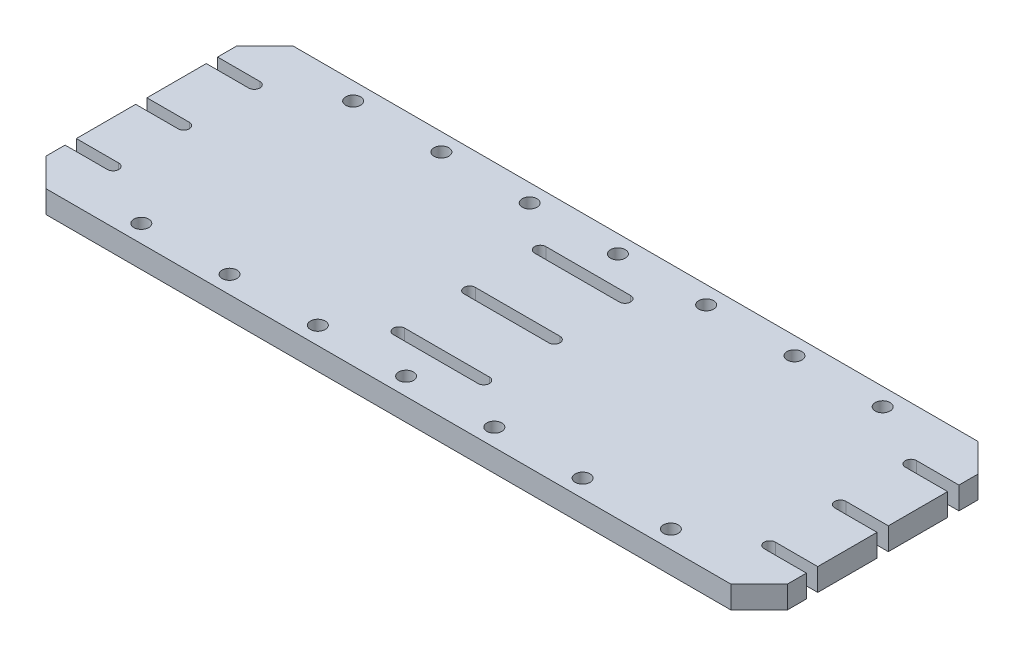
SolidWorks part; units mm, degrees
ref_plane "Front Plane" through (0, 0, 0) normal (0, 0, 1) x (1, 0, 0)
ref_plane "Top Plane" through (0, 0, 0) normal (0, 1, 0) x (1, 0, 0)
ref_plane "Right Plane" through (0, 0, 0) normal (1, 0, 0) x (0, 0, -1)
sketch "Sketch1" plane through (0, 0, 0) normal (0, 1, 0) x (1, 0, 0)
  line L1 (105, -35) -> (-105, -35)
  line L2 (105, -35) -> (105, 35)
  line L3 (105, 35) -> (-105, 35)
  line L4 (-105, -35) -> (-105, 35)
  line L5 (105, -35) -> (-105, 35) construction
  line L6 (105, 35) -> (-105, -35) construction
  point P0 (0, 0)
  dimension "D1" = 210
  dimension "D2" = 70
extrude "Boss-Extrude1" add sketch "Sketch1" along normal blind 6.35
sketch "Sketch3" plane through (0, 6.35, 0) normal (0, 1, 0) x (1, 0, 0)
  line L0 (12, 0) -> (-12, 0) construction
  line L1 (12, -1.6) -> (-12, -1.6)
  line L2 (12, 1.6) -> (-12, 1.6)
  arc A0 (12, -1.6) -> (12, 1.6) centre (12, 0) ccw
  arc A1 (-12, 1.6) -> (-12, -1.6) centre (-12, 0) ccw
  point P2 (0, 0)
  dimension "D1" = 3.2
  dimension "D2" = 24
extrude "Cut-Extrude1" cut sketch "Sketch3" against normal through all both and the other way through all
pattern_linear "LPattern1" count 4 spacing 20 along (0, 0, 1) count 4 spacing 20 along (0, 0, -1) of "Cut-Extrude1"
pattern_linear "LPattern2" count 2 spacing 105 along (1, 0, 0) count 2 spacing 105 along (-1, 0, 0) of "LPattern1", "Cut-Extrude1"
sketch "Sketch4" plane through (0, 6.35, 0) normal (0, 1, 0) x (1, 0, 0)
  circle A0 centre (0, 30) radius 2.1
  circle A1 centre (0, -30) radius 2.1
  circle A2 centre (0, 50) radius 2.1
  circle A3 centre (0, -50) radius 2.1
  dimension "D5" = 4.2
  dimension "D1" = 30
  dimension "D2" = 20
  dimension "D3" = 30
  dimension "D4" = 20
extrude "Cut-Extrude2" cut sketch "Sketch4" against normal through all both and the other way through all
pattern_linear "LPattern3" count 4 spacing 25 along (1, 0, 0) count 4 spacing 25 along (-1, 0, 0) of "Cut-Extrude2"
chamfer "Chamfer1" distance 8 angle 45 4 edges at (105, 3.175, -35) (105, 3.175, 35) (-105, 3.175, -35) (-105, 3.175, 35)
